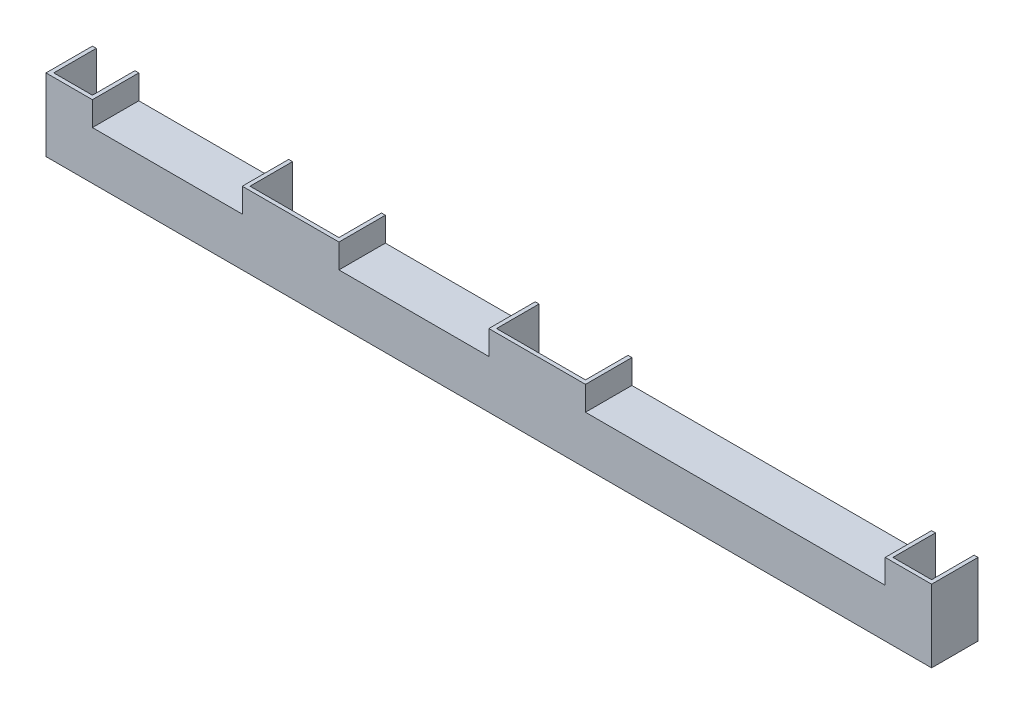
SolidWorks part; units mm, degrees
ref_plane "Front Plane" through (0, 0, 0) normal (0, 0, 1) x (1, 0, 0)
ref_plane "Top Plane" through (0, 0, 0) normal (0, 1, 0) x (1, 0, 0)
ref_plane "Right Plane" through (0, 0, 0) normal (1, 0, 0) x (0, 0, -1)
sketch "Sketch1" plane through (0, 0, 0) normal (0, 0, 1) x (1, 0, 0)
  line L0 (-916, 50) -> (-916, -50)
  line L1 (-916, -50) -> (916, -50)
  line L2 (916, -50) -> (916, 50)
  line L3 (916, 50) -> (-916, 50)
  point P2 (0, -50)
  point P5 (916, 0)
  dimension "D1" = 100
  dimension "D2" = 1832
extrude "Boss-Extrude1" add sketch "Sketch1" along normal blind 8
sketch "Sketch2" plane through (0, 0, 0) normal (0, 0, -1) x (-1, 0, 0)
  line L0 (-916, 50) -> (-916, -50)
  line L1 (-916, -50) -> (-908, -50)
  line L2 (916, -50) -> (-916, -50) construction
  line L3 (-908, -50) -> (-908, 50)
  line L4 (-916, 50) -> (916, 50) construction
  line L5 (-908, 50) -> (-916, 50)
  line L6 (916, 50) -> (908, 50)
  line L7 (908, 50) -> (908, -50)
  line L8 (908, -50) -> (916, -50)
  line L9 (916, -50) -> (916, 50)
  line L10 (820, 50) -> (820, -50)
  line L11 (828, 50) -> (828, -50)
  line L12 (828, -50) -> (820, -50)
  line L13 (820, 50) -> (828, 50)
  line L14 (510, 50) -> (510, -50)
  line L15 (502, 50) -> (502, -50)
  line L16 (310, 50) -> (310, -50)
  line L17 (318, 50) -> (318, -50)
  line L18 (310, -50) -> (318, -50)
  line L19 (310, 50) -> (318, 50)
  line L20 (502, 50) -> (510, 50)
  line L21 (502, -50) -> (510, -50)
  line L22 (0, 50) -> (0, -50)
  line L23 (-8, 50) -> (-8, -50)
  line L24 (-192, 50) -> (-192, -50)
  line L25 (-200, 50) -> (-200, -50)
  line L26 (-8, 50) -> (0, 50)
  line L27 (-8, -50) -> (0, -50)
  line L28 (-200, -50) -> (-192, -50)
  line L29 (-200, 50) -> (-192, 50)
  line L30 (-820, 50) -> (-820, -50)
  line L31 (-828, 50) -> (-828, -50)
  line L32 (-828, 50) -> (-820, 50)
  line L33 (-828, -50) -> (-820, -50)
  dimension "D1" = 8
  dimension "D2" = 8
  dimension "D3" = 88
  dimension "D4" = 8
  dimension "D5" = 310
  dimension "D6" = 8
  dimension "D7" = 200
  dimension "D8" = 8
  dimension "D9" = 310
  dimension "D10" = 200
  dimension "D11" = 8
  dimension "D12" = 8
  dimension "D13" = 620
  dimension "D14" = 8
extrude "Boss-Extrude2" add sketch "Sketch2" along normal blind 88
sketch "Sketch3" plane through (0, 50, 0) normal (0, 1, 0) x (1, 0, 0)
  line L0 (-916, 88) -> (-916, -8)
  line L1 (-916, 88) -> (-908, 88)
  line L2 (-908, 88) -> (-908, 0)
  line L3 (-908, 0) -> (-828, 0)
  line L4 (-828, 0) -> (-828, 88)
  line L5 (-828, 88) -> (-820, 88)
  line L6 (-820, 88) -> (-820, -8)
  line L7 (916, -8) -> (-916, -8) construction
  line L8 (-820, -8) -> (-916, -8)
  line L9 (-510, 88) -> (-510, -8)
  line L10 (-510, 88) -> (-502, 88)
  line L12 (-502, 88) -> (-502, 0)
  line L13 (-502, 0) -> (-318, 0)
  line L14 (-318, 0) -> (-318, 88)
  line L15 (-318, 88) -> (-310, 88)
  line L16 (-310, 88) -> (-310, -8)
  line L17 (-310, -8) -> (-510, -8)
  line L18 (0, 88) -> (0, -8)
  line L19 (0, 88) -> (8, 88)
  line L20 (8, 88) -> (8, 0)
  line L21 (8, 0) -> (192, 0)
  line L22 (192, 0) -> (192, 88)
  line L23 (192, 88) -> (200, 88)
  line L24 (200, 88) -> (200, -8)
  line L25 (200, -8) -> (0, -8)
  line L26 (820, 88) -> (820, -8)
  line L27 (820, 88) -> (828, 88)
  line L28 (828, 88) -> (828, 0)
  line L29 (828, 0) -> (908, 0)
  line L30 (908, 0) -> (908, 88)
  line L31 (908, 88) -> (916, 88)
  line L32 (916, 88) -> (916, -8)
  line L33 (916, -8) -> (820, -8)
extrude "Boss-Extrude3" add sketch "Sketch3" along normal blind 50
sketch "Sketch4" plane through (0, 0, 0) normal (0, 0, -1) x (-1, 0, 0)
  line L26 (-820, 50) -> (-820, 42)
  line L27 (-820, -50) -> (-820, 50) construction
  line L28 (-820, 42) -> (-200, 42)
  line L29 (-200, 50) -> (-200, -50) construction
  line L30 (-200, 42) -> (-200, 50)
  line L31 (-200, 50) -> (-820, 50)
  line L32 (0, 50) -> (0, 42)
  line L33 (0, -50) -> (0, 100) construction
  line L34 (0, 42) -> (310, 42)
  line L35 (310, 50) -> (310, -50) construction
  line L36 (310, 42) -> (310, 50)
  line L37 (310, 50) -> (0, 50)
  line L38 (510, 50) -> (510, 42)
  line L39 (510, -50) -> (510, 50) construction
  line L40 (510, 42) -> (820, 42)
  line L41 (820, 100) -> (820, -50) construction
  line L42 (820, 42) -> (820, 50)
  line L43 (820, 50) -> (510, 50)
  dimension "D1" = 8
extrude "Boss-Extrude4" add sketch "Sketch4" along normal up to surface (88 mm away) up to face at (-912, 25, -88)
